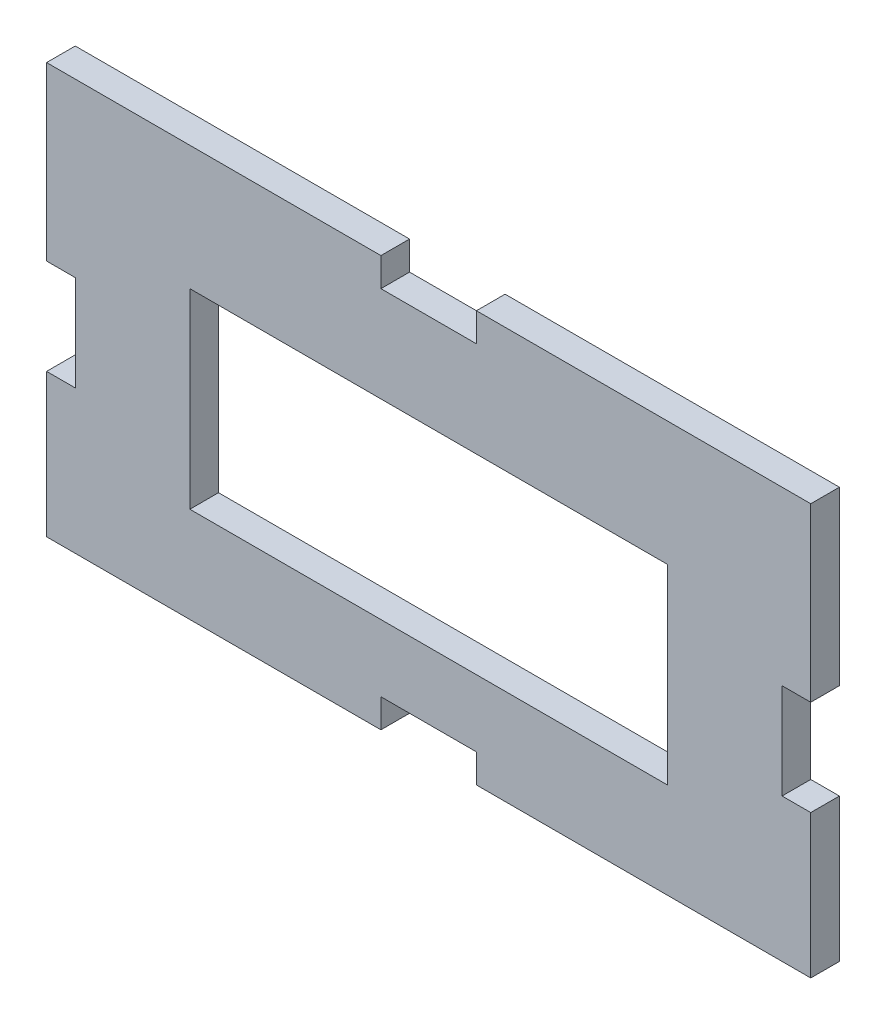
SolidWorks part; units mm, degrees
ref_plane "Front Plane" through (0, 0, 0) normal (0, 0, 1) x (1, 0, 0)
ref_plane "Top Plane" through (0, 0, 0) normal (0, 1, 0) x (1, 0, 0)
ref_plane "Right Plane" through (0, 0, 0) normal (1, 0, 0) x (0, 0, -1)
sketch "Sketch1" plane through (0, 0, 0) normal (0, 0, 1) x (1, 0, 0)
  line L0 (-32.6436, 0) -> (-32.6436, -18)
  line L1 (-32.6436, -18) -> (-29.6436, -18)
  line L2 (-29.6436, -18) -> (-29.6436, -28)
  line L3 (-29.6436, -28) -> (-32.6436, -28)
  line L4 (-32.6436, -28) -> (-32.6436, -43)
  line L5 (-32.6436, -43) -> (2.3564, -43)
  line L6 (47.3564, -43) -> (47.3564, -28)
  line L7 (47.3564, -28) -> (44.3564, -28)
  line L8 (44.3564, -28) -> (44.3564, -18)
  line L9 (44.3564, -18) -> (47.3564, -18)
  line L10 (47.3564, -18) -> (47.3564, -3)
  line L11 (-32.6436, 0) -> (2.3564, 0)
  line L12 (2.3564, 0) -> (2.3564, -3)
  line L13 (2.3564, -3) -> (12.3564, -3)
  line L16 (12.3564, -3) -> (12.3564, 0)
  line L17 (12.3564, 0) -> (47.3564, 0)
  line L18 (47.3564, 0) -> (47.3564, -3)
  line L19 (12.3564, -43) -> (47.3564, -43)
  line L21 (2.3564, -43) -> (2.3564, -40)
  line L22 (2.3564, -40) -> (12.3564, -40)
  line L23 (12.3564, -43) -> (12.3564, -40)
  point P4 (7.3564, -43)
extrude "Boss-Extrude1" add sketch "Sketch1" along normal blind 3
sketch "Sketch2" plane through (0, 0, 3) normal (0, 0, 1) x (1, 0, 0)
  line L0 (7.3564, -3) -> (7.3564, -40) construction
  line L1 (12.3564, -3) -> (2.3564, -3) construction
  line L2 (2.3564, -40) -> (12.3564, -40) construction
  line L3 (-29.6436, -23) -> (44.3564, -23) construction
  line L4 (-29.6436, -18) -> (-29.6436, -28) construction
  line L5 (44.3564, -28) -> (44.3564, -18) construction
  line L7 (-17.6436, -33) -> (32.3564, -33)
  line L8 (-17.6436, -33) -> (-17.6436, -13)
  line L9 (-17.6436, -13) -> (32.3564, -13)
  line L10 (32.3564, -33) -> (32.3564, -13)
  line L11 (-17.6436, -33) -> (32.3564, -13) construction
  line L12 (-17.6436, -13) -> (32.3564, -33) construction
  point P12 (7.3564, -23)
  dimension "D1" = 20
  dimension "D2" = 50
extrude "Cut-Extrude1" cut sketch "Sketch2" against normal blind 10
